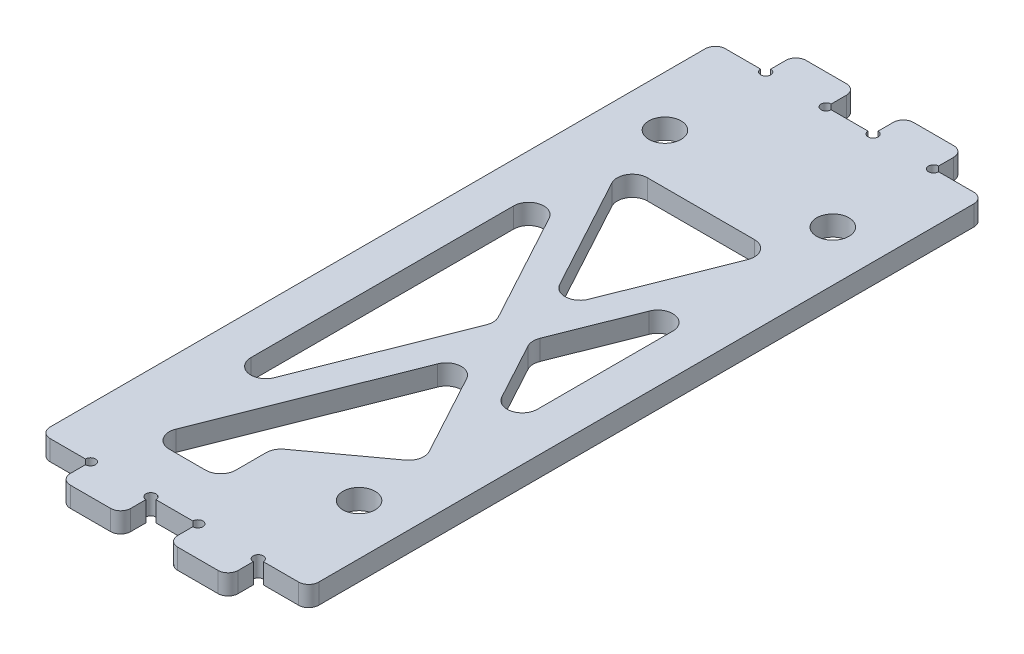
SolidWorks part; units mm, degrees
material "Thornel Mat VMA"
ref_plane "Front Plane" through (0, 0, 0) normal (0, 0, 1) x (1, 0, 0)
ref_plane "Top Plane" through (0, 0, 0) normal (0, 1, 0) x (1, 0, 0)
ref_plane "Right Plane" through (0, 0, 0) normal (1, 0, 0) x (0, 0, -1)
other "Configuration Table"
sketch "Sketch1" plane through (0, 0, 0) normal (0, 1, 0) x (1, 0, 0)
  line L0 (-5, -23.5132) -> (-12.0122, -23.5132) construction
  line L1 (0, 13) -> (6, 13)
  line L2 (0, 13) -> (0, 10)
  line L3 (0, 10) -> (6, 10)
  line L4 (6, 13) -> (6, 10)
  line L5 (10.6623, 13) -> (16.6623, 13)
  line L6 (10.6623, 13) -> (10.6623, 10)
  line L7 (10.6623, 10) -> (16.6623, 10)
  line L8 (16.6623, 13) -> (16.6623, 10)
  line L9 (16.6623, -60.0264) -> (16.6623, -57.0264)
  line L10 (10.6623, -57.0264) -> (16.6623, -57.0264)
  line L11 (10.6623, -60.0264) -> (10.6623, -57.0264)
  line L12 (10.6623, -60.0264) -> (16.6623, -60.0264)
  line L13 (6, -60.0264) -> (6, -57.0264)
  line L14 (0, -57.0264) -> (6, -57.0264)
  line L15 (0, -60.0264) -> (0, -57.0264)
  line L16 (0, -60.0264) -> (6, -60.0264)
  line B0 (-5, 10) -> (-5, -57.0264)
  line B1 (-5, -57.0264) -> (21.6623, -57.0264)
  line B2 (21.6623, -57.0264) -> (21.6623, 10)
  line B3 (21.6623, 10) -> (-5, 10)
  line B4 (0, 13) -> (0, 10)
  line B5 (6, 10) -> (6, 13)
  line B6 (16.6623, 10) -> (16.6623, 13)
  line B7 (10.6623, 13) -> (10.6623, 10)
  circle B8 centre (0, 0) radius 1.6
  circle B9 centre (16.6623, 0) radius 1.6
  circle B10 centre (16.6623, -47.0264) radius 1.6
sketch_block_instance "Block4-1"
sketch_block "Block4"
extrude "Boss-Extrude1" add sketch "Sketch1" along normal blind 2 contours B2 B3 L7 L3 B0 B1 L14 L10 B10 B9 B8 | L8 L5 L6 L7 | L4 L1 L2 L3 | L15 L16 L13 L14 | L11 L12 L9 L10
fillet "Fillet1" radius 1 12 edges at (21.6623, 1, 57.0264) (16.6623, 1, 60.0264) (10.6623, 1, 60.0264) (6, 1, 60.0264) (0, 1, 60.0264) (-5, 1, 57.0264) (-5, 1, -10) (0, 1, -13) (6, 1, -13) (10.6623, 1, -13) (16.6623, 1, -13) (21.6623, 1, -10)
sketch "Sketch3" plane through (0, 0, 0) normal (0, -1, 0) x (1, 0, 0)
  circle A0 centre (0, 57.0264) radius 0.5
  circle A1 centre (6, 57.0264) radius 0.5
  circle A2 centre (10.6623, 57.0264) radius 0.5
  circle A3 centre (16.6623, 57.0264) radius 0.5
  circle A4 centre (0, -10) radius 0.5
  circle A5 centre (6, -10) radius 0.5
  circle A6 centre (10.6623, -10) radius 0.5
  circle A7 centre (16.6623, -10) radius 0.5
  dimension "D1" = 1
extrude "Cut-Extrude1" cut sketch "Sketch3" against normal blind 2
sketch "Sketch4" plane through (0, 2, 0) normal (0, 1, 0) x (1, 0, 0)
  line L0 (21.6623, -56.0264) -> (21.6623, 9) construction
  line L1 (7.9273, -52.0264) -> (-1, -52.0264)
  line L2 (7.9273, -52.0264) -> (7.9273, -4.963)
  line L3 (7.9273, -4.963) -> (-1, -4.963)
  line L4 (-1, -52.0264) -> (-1, -4.963)
  line L5 (7.9273, -4.963) -> (17.6623, -4.963)
  line L6 (7.9273, -4.963) -> (7.9273, -39.6516)
  line L7 (7.9273, -39.6516) -> (17.6623, -39.6516)
  line L8 (17.6623, -4.963) -> (17.6623, -39.6516)
  line L9 (-5, 9) -> (-5, -56.0264) construction
  line L10 (-4, -57.0264) -> (-0.5, -57.0264) construction
  line L11 (7.9273, -46.7594) -> (17.6623, -39.6516)
  point P14 (7.9273, -46.7594)
  point P15 (17.4491, -39.6516)
  dimension "D1" = 4
  dimension "D2" = 4
  dimension "D3" = 5
extrude "Cut-Extrude2" cut sketch "Sketch4" against normal blind 2 contours L4 L1 L2 L3 | L8 L5 L2 L7 | L2 L11 L7
sketch "Sketch6" plane through (0, 2, 0) normal (0, 1, 0) x (1, 0, 0)
  line L0 (-1, -4.963) -> (18.4998, -40.9313)
  line L1 (17.6623, -4.963) -> (-1, -52.0264)
  point P8 (18.4998, -40.9313)
extrude "Extrude-Thin1" add sketch "Sketch6" against normal blind 2 thin thin type mid plane wall 3
fillet "Fillet2" radius 1.5 14 edges at (17.6623, 1, 36.2392) (11.4313, 1, 24.7459) (17.6623, 1, 9.0323) (7.9273, 1, 46.7594) (7.9273, 1, 52.0264) (0.6136, 1, 52.0264) (9.9897, 1, 28.3813) (16.5429, 1, 40.4689) (16.0487, 1, 4.963) (9.5674, 1, 21.3078) (8.1258, 1, 24.9432) (-1, 1, 47.9571) (-1, 1, 8.1103) (0.7063, 1, 4.963)
